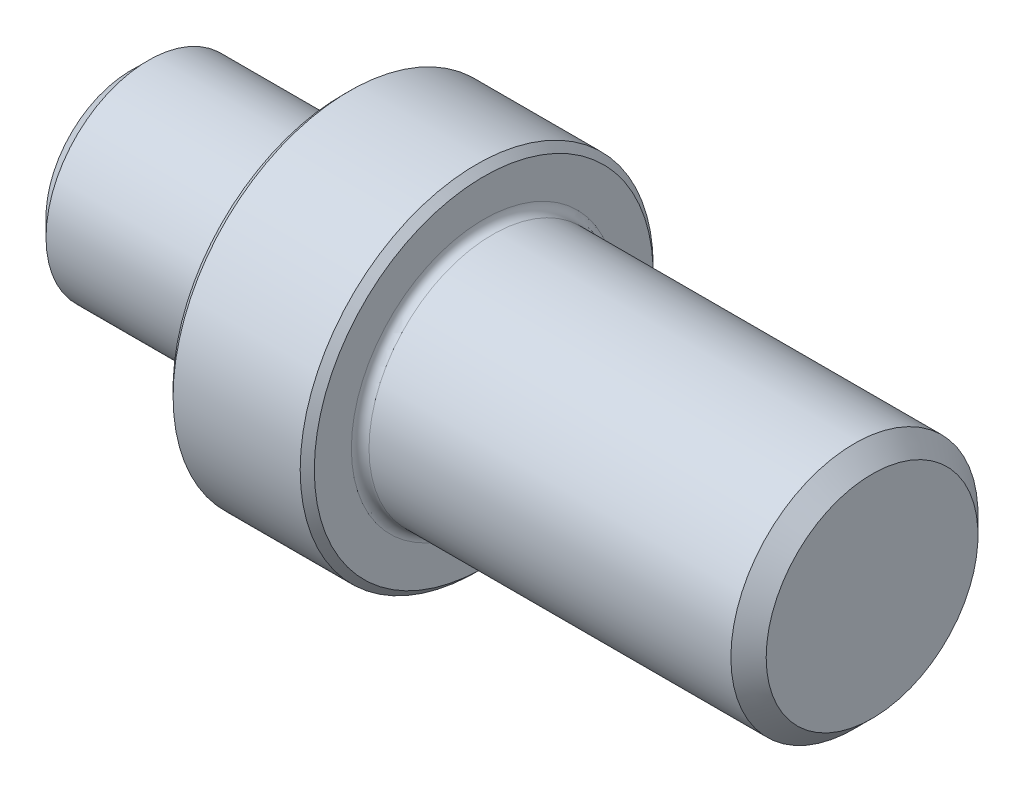
SolidWorks part; units mm, degrees
material "1.0570 (S355J2G3)"
ref_plane "Front Plane" through (0, 0, 0) normal (0, 0, 1) x (1, 0, 0)
ref_plane "Top Plane" through (0, 0, 0) normal (0, 1, 0) x (1, 0, 0)
ref_plane "Right Plane" through (0, 0, 0) normal (1, 0, 0) x (0, 0, -1)
sketch "Sketch1" plane through (0, 0, 0) normal (0, 0, 1) x (1, 0, 0)
  line L0 (-85.4522, 0) -> (285.8875, 0) construction
  line L1 (0, 0) -> (0, 29)
  line L2 (0, 29) -> (60, 29)
  line L3 (60, 29) -> (60, 50)
  line L4 (60, 50) -> (100, 50)
  line L5 (100, 50) -> (100, 35)
  line L6 (100, 35) -> (210, 35)
  line L7 (210, 35) -> (210, 0)
  line L8 (0, 0) -> (210, 0)
  dimension "D1" = 58
  dimension "D2" = 100
  dimension "D3" = 70
  dimension "D4" = 60
  dimension "D5" = 100
  dimension "D6" = 210
revolve "Revolve1" add sketch "Sketch1" angle 360 about L8
chamfer "Chamfer1" distance 5 angle 45 2 edges at (210, 0, 35) (0, 0, 29)
chamfer "Chamfer2" distance 2 angle 45 2 edges at (100, 0, 50) (60, 0, 50)
fillet "Fillet1" radius 2.5 2 edges at (100, 0, 35) (60, 0, 29)
